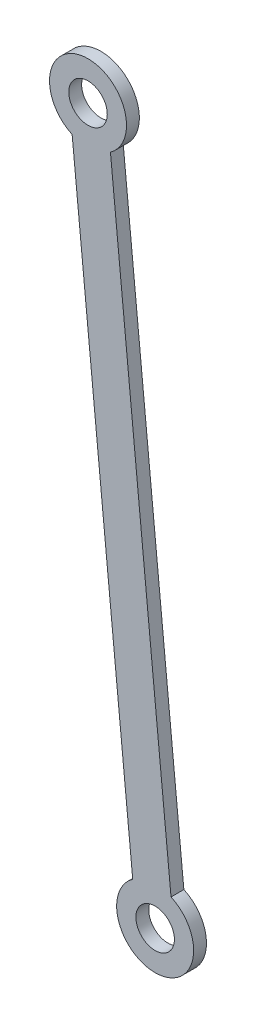
SolidWorks part; units mm, degrees
ref_plane "Front Plane" through (0, 0, 0) normal (0, 0, 1) x (1, 0, 0)
ref_plane "Top Plane" through (0, 0, 0) normal (0, 1, 0) x (1, 0, 0)
ref_plane "Right Plane" through (0, 0, 0) normal (1, 0, 0) x (0, 0, -1)
sketch "Sketch1" plane through (0, 0, 0) normal (0, 0, 1) x (1, 0, 0)
  line L0 (33.7318, 59.8603) -> (18.0408, 219.089) construction
  line L1 (33.7318, 59.8603) -> (18.0408, 219.089) construction
  line L2 (33.7318, 59.8603) -> (18.0408, 219.089) construction
  line L3 (29.2535, 59.419) -> (13.5625, 218.6477)
  line L4 (38.2101, 60.3016) -> (22.5191, 219.5303)
  circle A0 centre (18.0408, 219.089) radius 9
  circle A1 centre (33.7318, 59.8603) radius 9
  arc A2 (29.2535, 59.419) -> (38.2101, 60.3016) centre (33.7318, 59.8603) ccw
  arc A3 (22.5191, 219.5303) -> (13.5625, 218.6477) centre (18.0408, 219.089) ccw
  arc A4 (22.5191, 219.5303) -> (13.5625, 218.6477) centre (18.0408, 219.089) cw
  arc A5 (38.2101, 60.3016) -> (29.2535, 59.419) centre (33.7318, 59.8603) ccw
  point P5 (25.8863, 139.4746)
  dimension "D1" = 18
  dimension "D2" = 9
extrude "Boss-Extrude1" add sketch "Sketch1" against normal blind 3 contours A3 L4 A0 L3 | L4 A4 L3 A0 | A1 L4 A0 L3 | A2 L3 A1 L4 | A5 L4 A1 L3
